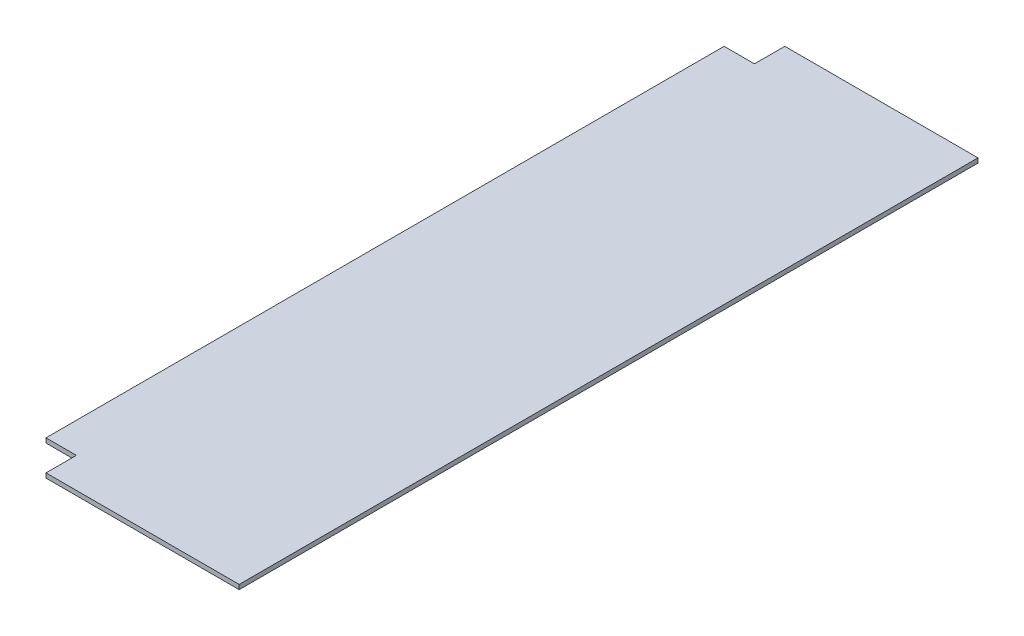
SolidWorks part; units mm, degrees
ref_plane "Front Plane" through (0, 0, 0) normal (0, 0, 1) x (1, 0, 0)
ref_plane "Top Plane" through (0, 0, 0) normal (0, 1, 0) x (1, 0, 0)
ref_plane "Right Plane" through (0, 0, 0) normal (1, 0, 0) x (0, 0, -1)
sketch "Sketch1" plane through (0, 0, 0) normal (0, 1, 0) x (1, 0, 0)
  line L13 (-66.9625, 365) -> (123.9175, 365)
  line L14 (-96.9625, 335) -> (-96.9625, -335)
  line L15 (-66.9625, -365) -> (123.9175, -365)
  line L16 (123.9175, 365) -> (123.9175, -365)
  line L19 (-96.9625, 335) -> (-66.9625, 335)
  line L20 (-66.9625, 365) -> (-66.9625, 335)
  line L23 (-96.9625, -335) -> (-66.9625, -335)
  line L24 (-66.9625, -365) -> (-66.9625, -335)
  dimension "D1" = 190.88
  dimension "D3" = 365
  dimension "D4" = 30
  dimension "D5" = 30
  dimension "D6" = 30
  dimension "D7" = 30
extrude "Boss-Extrude1" add sketch "Sketch1" along normal blind 4.5
